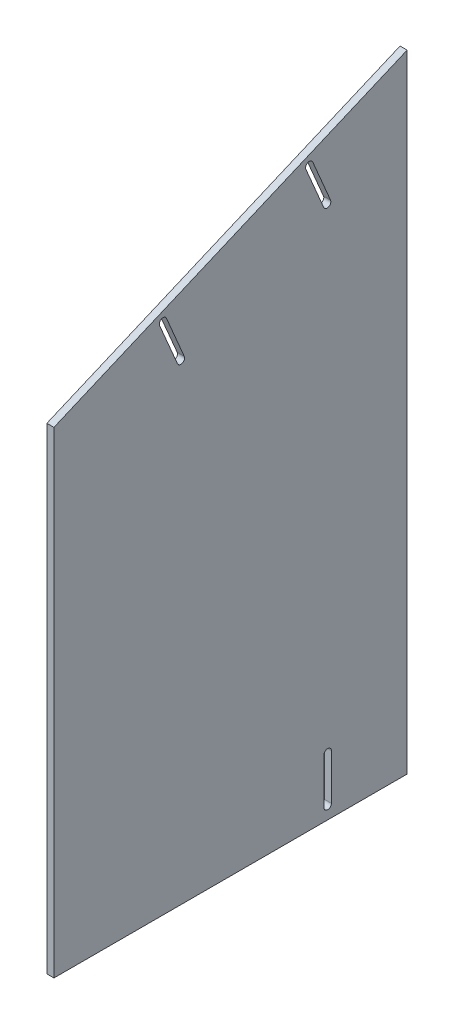
SolidWorks part; units mm, degrees
ref_plane "Front Plane" through (0, 0, 0) normal (1, 0, 0) x (0, 1, 0)
ref_plane "Top Plane" through (0, 0, 0) normal (0, 0, 1) x (0, 1, 0)
ref_plane "Right Plane" through (0, 0, 0) normal (0, 1, 0) x (-1, 0, 0)
sketch "Sketch1" plane through (0, 0, 0) normal (1, 0, 0) x (0, 1, 0)
  line L0 (-85, 200) -> (0, 0)
  line L1 (0, 0) -> (-355, 0)
  line L2 (-355, 0) -> (-355, 200)
  line L3 (-355, 200) -> (-85, 200)
  line L4 (-322.1, 45) -> (-347.9, 45) construction
  line L5 (-322.1, 47.1) -> (-347.9, 47.1)
  line L6 (-322.1, 42.9) -> (-347.9, 42.9)
  line L7 (-64.1775, 138.2228) -> (-87.9221, 128.1314) construction
  line L8 (-64.9989, 140.1555) -> (-88.7434, 130.0641)
  line L9 (-63.3561, 136.2901) -> (-87.1007, 126.1987)
  line L10 (-41.9745, 98.7636) -> (-61.8398, 90.3209) construction
  line L11 (-28.9749, 55.393) -> (-52.7194, 45.3016) construction
  line L12 (-28.1535, 53.4603) -> (-51.898, 43.3689)
  line L13 (-29.7963, 57.3257) -> (-53.5408, 47.2343)
  arc A0 (-322.1, 47.1) -> (-322.1, 42.9) centre (-322.1, 45) cw
  arc A1 (-347.9, 42.9) -> (-347.9, 47.1) centre (-347.9, 45) cw
  arc A2 (-64.9989, 140.1555) -> (-63.3561, 136.2901) centre (-64.1775, 138.2228) cw
  arc A3 (-87.1007, 126.1987) -> (-88.7434, 130.0641) centre (-87.9221, 128.1314) cw
  arc A4 (-28.1535, 53.4603) -> (-29.7963, 57.3257) centre (-28.9749, 55.393) ccw
  arc A5 (-53.5408, 47.2343) -> (-51.898, 43.3689) centre (-52.7194, 45.3016) ccw
  point P7 (-335, 45)
  point P14 (-76.0498, 133.1771)
  point P23 (-40.8471, 50.3473)
  dimension "D4" = 30
  dimension "D8" = 5
  dimension "D1" = 200
  dimension "D2" = 355
  dimension "D3" = 270
  dimension "D5" = 4.2
  dimension "D6" = 5
  dimension "D7" = 45
  dimension "D9" = 90
  dimension "D10" = 65
extrude "Boss-Extrude1" add sketch "Sketch1" along normal blind 4
